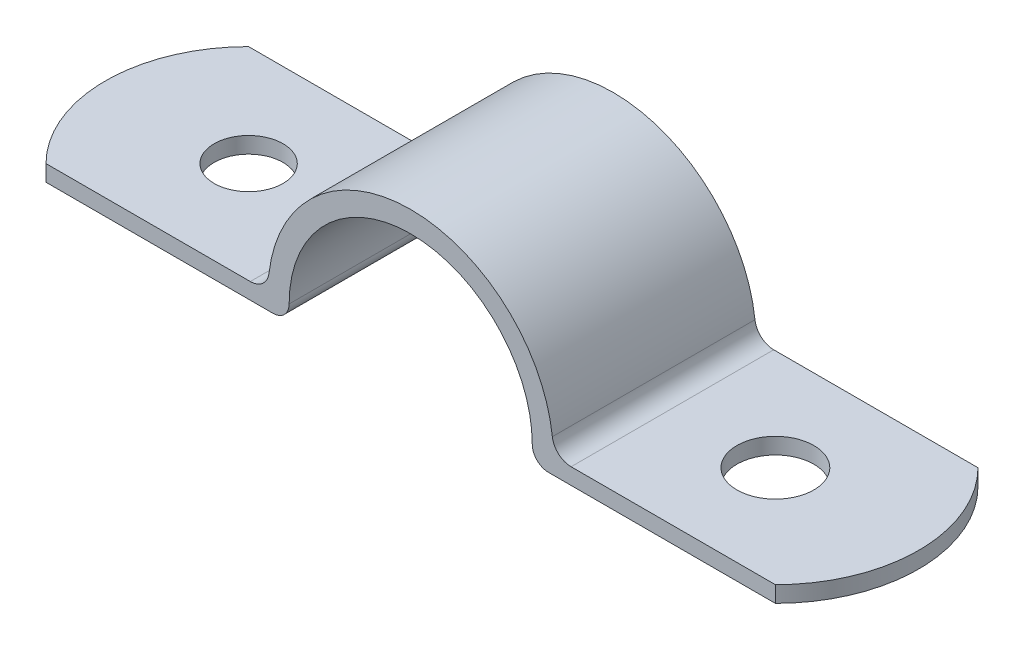
SolidWorks part; units mm, degrees
ref_plane "前视基准面" through (0, 0, 0) normal (0, 0, 1) x (1, 0, 0)
ref_plane "上视基准面" through (0, 0, 0) normal (0, 1, 0) x (1, 0, 0)
ref_plane "右视基准面" through (0, 0, 0) normal (1, 0, 0) x (0, 0, -1)
sketch "草图1" plane through (0, 0, 0) normal (0, 1, 0) x (1, 0, 0)
  line L1 (0, -10) -> (12, -10)
  line L2 (12, -10) -> (12, 0)
  line L3 (12, 0) -> (0, 0)
  line L5 (24, -10) -> (24, 0)
  line L6 (24, 0) -> (36, 0)
  line L9 (24, -10) -> (36, -10)
  circle A1 centre (5, -5) radius 1.7
  arc A2 (0, -10) -> (0, 0) centre (5, -5) cw
  circle A3 centre (31, -5) radius 1.9
  arc A4 (36, 0) -> (36, -10) centre (31, -5) cw
extrude "凸台-拉伸1" add sketch "草图1" along normal blind 0.8
sketch "草图2" plane through (0, 0, 10) normal (0, 0, 1) x (1, 0, 0)
  line L12 (0, 0.8) -> (12, 0.8) construction
  line L13 (10.0829, 0.8) -> (12, 0.8)
  line L14 (0, 0) -> (12, 0) construction
  line L15 (25.9171, 0.8) -> (24, 0.8)
  line L16 (24, 0.8) -> (36, 0.8) construction
  line L17 (24, 0) -> (36, 0) construction
  arc A3 (24, 0.8) -> (12, 0.8) centre (18, 0.8) ccw
  arc A4 (11.0079, 1.6226) -> (24.9921, 1.6226) centre (18, 0.8) cw
  arc A5 (11.0079, 1.6226) -> (10.0829, 0.8) centre (10.0829, 1.7314) cw
  arc A7 (12, 0.8) -> (11.2, 0) centre (11.2, 0.8) cw
  arc A8 (24.9921, 1.6226) -> (25.9171, 0.8) centre (25.9171, 1.7314) ccw
  arc A9 (24, 0.8) -> (24.8, 0) centre (24.8, 0.8) ccw
  line M10 (12, 0.8) -> (0, 0.8)
extrude "凸台-拉伸5" add sketch "草图2" against normal blind 10 contours A8 A4 A5 A3 L15 M10
sketch "草图3" plane through (0, 0, 10) normal (0, 0, 1) x (1, 0, 0)
  line L1 (0, 0) -> (12, 0) construction
  line L3 (11.2, 0) -> (12, 0)
  line L4 (12, 0) -> (12, 0.8)
  arc A0 (12, 0.8) -> (11.2, 0) centre (11.2, 0.8) cw
extrude "切除-拉伸3" cut sketch "草图3" against normal blind 10 contours A0 L3 L4
sketch "草图4" plane through (0, 0, 10) normal (0, 0, 1) x (1, 0, 0)
  line L1 (24, 0) -> (36, 0) construction
  line L2 (24, 0.8) -> (24, 0)
  line L3 (24, 0) -> (24.8, 0)
  arc A0 (24, 0.8) -> (24.8, 0) centre (24.8, 0.8) ccw
extrude "切除-拉伸4" cut sketch "草图4" against normal blind 10 contours L2 L3 A0
